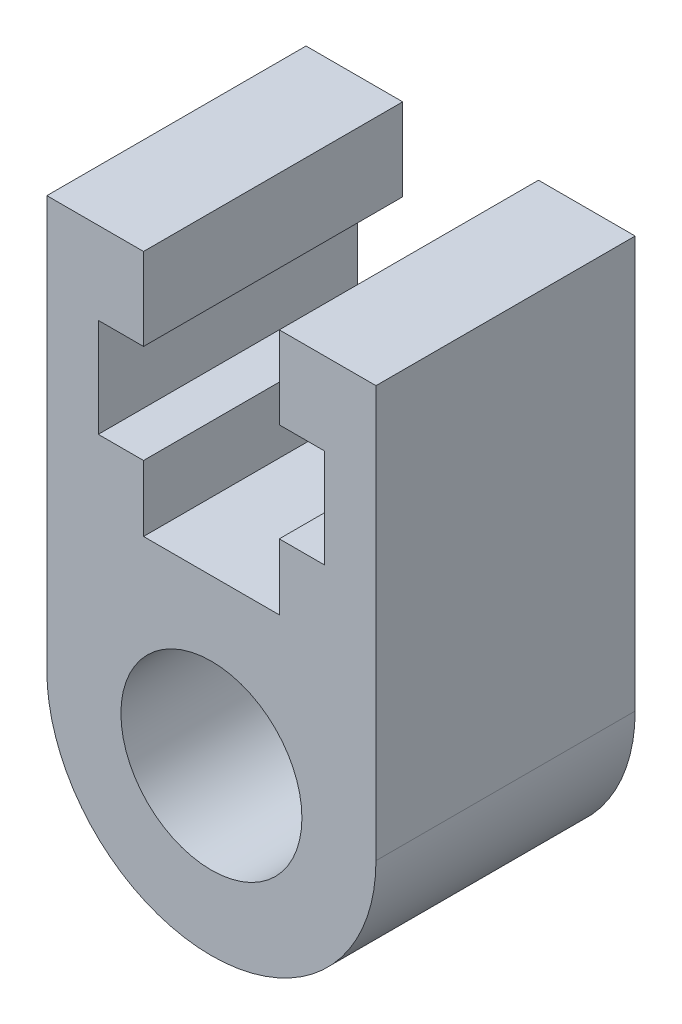
SolidWorks part; units mm, degrees
ref_plane "Front Plane" through (0, 0, 0) normal (0, 0, 1) x (1, 0, 0)
ref_plane "Top Plane" through (0, 0, 0) normal (0, 1, 0) x (1, 0, 0)
ref_plane "Right Plane" through (0, 0, 0) normal (1, 0, 0) x (0, 0, -1)
sketch "Sketch1" plane through (0, 0, 0) normal (0, 0, 1) x (1, 0, 0)
  line L0 (-4, 0) -> (-4, 10)
  line L1 (-4, 10) -> (-1.65, 10)
  line L2 (-1.65, 10) -> (-1.65, 8)
  line L3 (-1.65, 8) -> (-2.75, 8)
  line L4 (-2.75, 8) -> (-2.75, 5.6)
  line L5 (-2.75, 5.6) -> (-1.65, 5.6)
  line L6 (-1.65, 5.6) -> (-1.65, 4)
  line L7 (-1.65, 4) -> (1.65, 4)
  line L8 (0, 0) -> (0, 4) construction
  line L9 (1.65, 5.6) -> (1.65, 4)
  line L10 (2.75, 5.6) -> (1.65, 5.6)
  line L11 (2.75, 8) -> (2.75, 5.6)
  line L12 (1.65, 8) -> (2.75, 8)
  line L13 (1.65, 10) -> (1.65, 8)
  line L14 (4, 10) -> (1.65, 10)
  line L15 (4, 0) -> (4, 10)
  circle A0 centre (0, 0) radius 2.2
  arc A1 (-4, 0) -> (4, 0) centre (0, 0) ccw
  point P5 (0, 0)
  dimension "D1" = 4.4
  dimension "D2" = 4
  dimension "D3" = 1.65
  dimension "D4" = 2.4
  dimension "D5" = 2.75
  dimension "D6" = 2
  dimension "D7" = 6
  dimension "D8" = 10
extrude "Boss-Extrude1" add sketch "Sketch1" along normal blind 6.3
